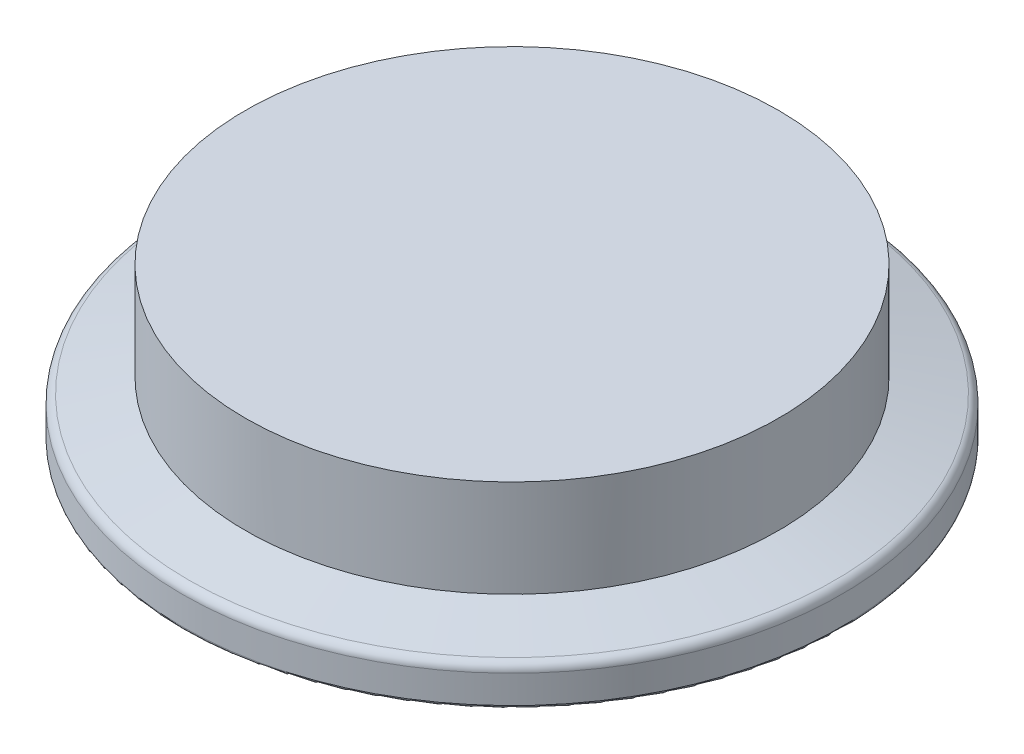
SolidWorks part; units mm, degrees
material "AISI 304"
ref_plane "Front Plane" through (0, 0, 0) normal (0, 0, 1) x (1, 0, 0)
ref_plane "Top Plane" through (0, 0, 0) normal (0, 1, 0) x (1, 0, 0)
ref_plane "Right Plane" through (0, 0, 0) normal (1, 0, 0) x (0, 0, -1)
sketch "Sketch1" plane through (0, 0, 0) normal (1, 0, 0) x (0, 0, -1)
  line L0 (0, 0) -> (0, 5.1) construction
  line L1 (-27.5, 0) -> (-27.5, 3.175)
  line L2 (-27.5, 3.175) -> (-20.3158, 5.1)
  line L6 (0, 2.5) -> (-20.625, 2.5)
  line L7 (-20.625, 2.5) -> (-20.625, 0)
  line L8 (-20.625, 0) -> (-27.5, 0)
  line L9 (-20.3158, 5.1) -> (0, 5.1)
  line L10 (0, 5.1) -> (0, 2.5)
  dimension "D1" = 75
  dimension "D2" = 40.6316
  dimension "Flange ID" = 41.25
  dimension "Flange OD" = 55
  dimension "D5" = 3.175
  dimension "Flange Height" = 5.1
  dimension "D9" = 2.5
revolve "Flange" add sketch "Sketch1" angle 360 about L0
sketch "Sketch2" plane through (0, 0, 0) normal (1, 0, 0) x (0, 0, -1)
  line L0 (0, 2.5) -> (-20.625, 2.5) construction
  line L1 (0, 0) -> (-15.85, 0)
  line L2 (0, 0) -> (0, 2.5)
  line L3 (0, 2.5) -> (-15.85, 2.5)
  line L4 (-15.85, 0) -> (-15.85, 2.5)
  line L5 (0, 0) -> (0, -4.8376) construction
  dimension "ID" = 31.7
revolve "Blank Insert" add sketch "Sketch2" angle 360 about L5
sketch "Sketch5" plane through (0, 2.5, 0) normal (0, -1, 0) x (1, 0, 0)
  circle A0 centre (0, 0) radius 22.25
  dimension "D1" = 44.5
extrude "Stub" add sketch "Sketch5" against normal offset from surface (10.2 mm away) 12.7 up to face at (0, 0, -20.625)
ref_plane "Plane1" through (0, -1.905, 0) normal (0, -1, 0) x (-1, 0, 0)
ref_plane "Plane2" through (0, 2.5, 0) normal (0, -1, 0) x (-1, 0, 0)
ref_plane "Plane3" through (0, 5.1, 0) normal (0, -1, 0) x (-1, 0, 0)
fillet "Fillet1" radius 0.762 1 edges at (0, 3.175, -27.5)
fillet "Fillet2" radius 0.254 1 edges at (0, 0, -27.5)
sketch "Sketch7" plane through (0, 12.7, 0) normal (0, 1, 0) x (1, 0, 0)
  line L0 (0, 22.25) -> (0, -22.25) construction
  line L1 (22.25, 0) -> (-22.25, 0) construction
  line L2 (0, 0) -> (0, 13.5) construction
  circle A0 centre (0, 0) radius 22.25 construction
  circle A1 centre (0, 0) radius 22.25 construction
  circle A2 centre (0, 13.5) radius 1.87
  circle A3 centre (13.5, 0) radius 1.87
  circle A4 centre (0, -13.5) radius 1.87
  circle A5 centre (-13.5, 0) radius 1.87
  circle A6 centre (0, 0) radius 1.397
  dimension "D1" = 4
  dimension "D2" = 13.5
